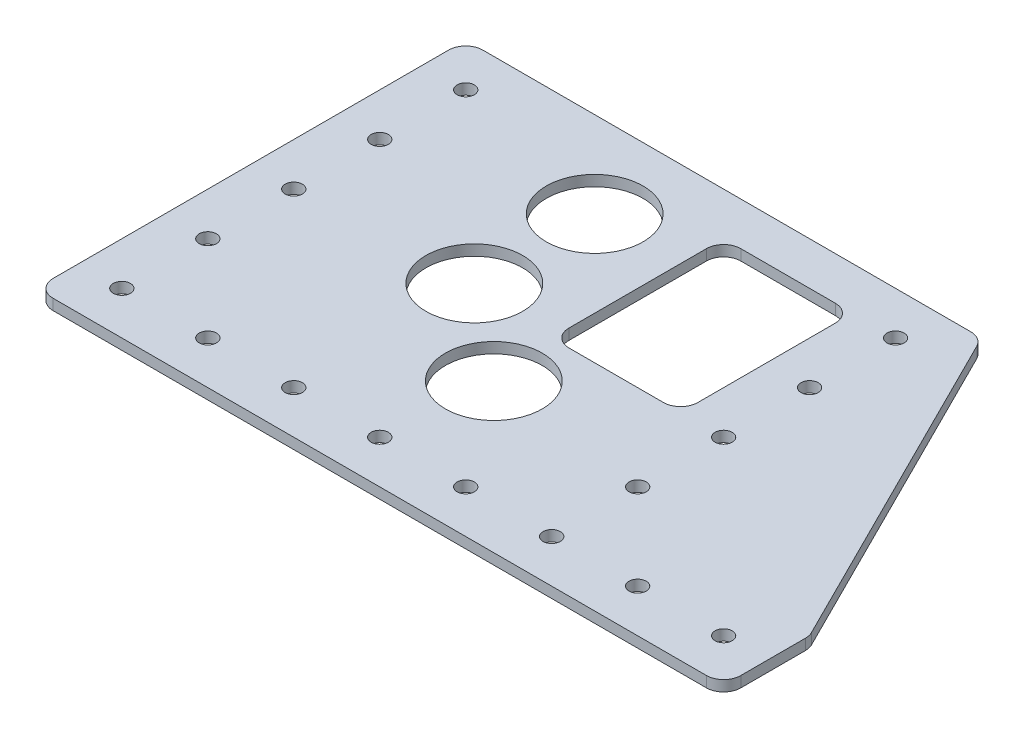
SolidWorks part; units mm, degrees
ref_plane "Front Plane" through (0, 0, 0) normal (0, 0, 1) x (1, 0, 0)
ref_plane "Top Plane" through (0, 0, 0) normal (0, 1, 0) x (1, 0, 0)
ref_plane "Right Plane" through (0, 0, 0) normal (1, 0, 0) x (0, 0, -1)
sketch "Sketch1" plane through (0, 0, 0) normal (0, 1, 0) x (1, 0, 0)
  line L0 (0, 5.08) -> (0, 121.92)
  line L1 (5.08, 127) -> (149.2604, 127)
  line L2 (153.8041, 124.1918) -> (202.6637, 26.4726)
  line L3 (203.2, 24.2008) -> (203.2, 5.08)
  line L4 (198.12, 0) -> (5.08, 0)
  line L5 (190.5, 12.7) -> (165.1, 12.7) construction
  line L6 (12.7, 12.7) -> (12.7, 38.1) construction
  line L8 (93.98, 114.3) -> (121.92, 114.3)
  line L9 (88.9, 109.22) -> (88.9, 68.58)
  line L10 (93.98, 63.5) -> (121.92, 63.5)
  line L11 (127, 109.22) -> (127, 68.58)
  line L12 (107.95, 63.5) -> (107.95, 114.3) construction
  line L13 (88.9, 88.9) -> (127, 88.9) construction
  circle A0 centre (190.5, 12.7) radius 2.54
  circle A1 centre (165.1, 12.7) radius 2.54
  circle A2 centre (139.7, 12.7) radius 2.54
  circle A3 centre (114.3, 12.7) radius 2.54
  circle A4 centre (88.9, 12.7) radius 2.54
  circle A5 centre (63.5, 12.7) radius 2.54
  circle A6 centre (38.1, 12.7) radius 2.54
  circle A7 centre (12.7, 12.7) radius 2.54
  circle A8 centre (12.7, 38.1) radius 2.54
  circle A9 centre (139.7, 38.1) radius 2.54
  circle A10 centre (12.7, 63.5) radius 2.54
  circle A11 centre (139.7, 63.5) radius 2.54
  circle A12 centre (12.7, 88.9) radius 2.54
  circle A13 centre (139.7, 88.9) radius 2.54
  circle A14 centre (12.7, 114.3) radius 2.54
  circle A15 centre (139.7, 114.3) radius 2.54
  circle A16 centre (63.5, 101.6) radius 14.3002
  circle A17 centre (63.5, 66.04) radius 14.3002
  circle A18 centre (91.3602, 43.942) radius 14.3002
  arc A19 (121.92, 114.3) -> (127, 109.22) centre (121.92, 109.22) cw
  arc A20 (121.92, 63.5) -> (127, 68.58) centre (121.92, 68.58) ccw
  arc A21 (88.9, 68.58) -> (93.98, 63.5) centre (93.98, 68.58) ccw
  arc A22 (93.98, 114.3) -> (88.9, 109.22) centre (93.98, 109.22) ccw
  arc A23 (0, 5.08) -> (5.08, 0) centre (5.08, 5.08) ccw
  arc A24 (203.2, 5.08) -> (198.12, 0) centre (198.12, 5.08) cw
  arc A25 (202.6637, 26.4726) -> (203.2, 24.2008) centre (198.12, 24.2008) cw
  arc A26 (149.2604, 127) -> (153.8041, 124.1918) centre (149.2604, 121.92) cw
  arc A27 (0, 121.92) -> (5.08, 127) centre (5.08, 121.92) cw
  point P48 (98.3069, 96.6343)
  point P51 (127, 114.3)
  point P54 (107.95, 88.9)
  point P59 (127, 63.5)
  point P64 (88.9, 114.3)
  point P67 (0, 0)
  point P70 (203.2, 0)
  point P73 (203.2, 25.4)
  point P76 (152.4, 127)
  point P79 (0, 127)
  dimension "D5" = 12.7
  dimension "D6" = 12.7
  dimension "D7" = 5.08
  dimension "D12" = 28.6004
  dimension "D22" = 5.08
  dimension "D23" = 5.08
  dimension "D1" = 127
  dimension "D2" = 203.2
  dimension "D3" = 152.4
  dimension "D4" = 25.4
  dimension "D9" = 25.4
  dimension "D11" = 25.4
  dimension "D13" = 63.5
  dimension "D14" = 25.4
  dimension "D15" = 35.56
  dimension "D16" = 83.058
  dimension "D17" = 35.56
  dimension "D18" = 38.1
  dimension "D19" = 50.8
  dimension "D20" = 63.5
  dimension "D21" = 25.4
  dimension "D8" = 8
  dimension "D10" = 5
extrude "Boss-Extrude1" add sketch "Sketch1" along normal blind 3.175
